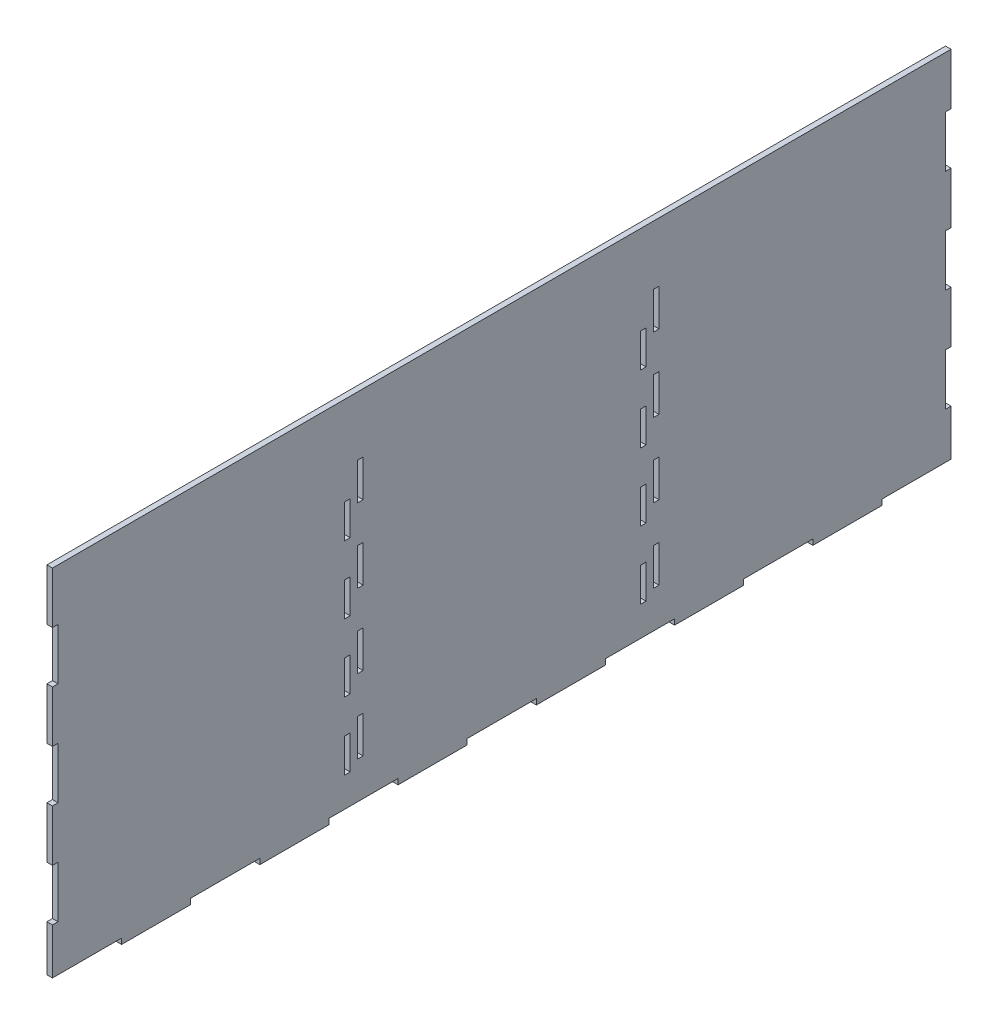
SolidWorks part; units mm, degrees
material "Acrylic (Medium-high impact)"
ref_plane "Front Plane" through (0, 0, 0) normal (0, 0, 1) x (1, 0, 0)
ref_plane "Top Plane" through (0, 0, 0) normal (0, 1, 0) x (1, 0, 0)
ref_plane "Right Plane" through (0, 0, 0) normal (1, 0, 0) x (0, 0, -1)
sketch "Sketch1" plane through (0, 0, 0) normal (1, 0, 0) x (0, 0, -1)
  line L0 (0, 152.4) -> (0, -152.4) construction
  line L1 (-381, 152.4) -> (381, 152.4)
  line L2 (-381, 152.4) -> (-381, -152.4)
  line L3 (-381, -152.4) -> (381, -152.4)
  line L4 (381, 152.4) -> (381, -152.4)
  line L5 (-381, 108.1768) -> (-381, 63.9536)
  line L10 (-381, 152.4) -> (-385.7625, 152.4)
  line L11 (-381, 152.4) -> (-381, 108.1768)
  line L12 (-381, 108.1768) -> (-385.7625, 108.1768)
  line L13 (-385.7625, 152.4) -> (-385.7625, 108.1768)
  line L14 (381, 152.4) -> (385.7625, 152.4)
  line L15 (381, 152.4) -> (381, 108.1768)
  line L16 (381, 108.1768) -> (385.7625, 108.1768)
  line L17 (385.7625, 152.4) -> (385.7625, 108.1768)
  line L18 (-385.7625, -152.4) -> (-326.4144, -152.4)
  line L19 (-385.7625, -152.4) -> (-385.7625, -157.1625)
  line L20 (-385.7625, -157.1625) -> (-326.4144, -157.1625)
  line L21 (-326.4144, -152.4) -> (-326.4144, -157.1625)
  line L22 (-381, 108.1768) -> (-385.7625, 108.1768)
  line L23 (-385.7625, 108.1768) -> (-385.7625, 63.9536)
  line L24 (-381, 63.9536) -> (-385.7625, 63.9536)
  line L25 (381, 108.1768) -> (381, 63.9536)
  line L26 (381, 108.1768) -> (385.7625, 108.1768)
  line L27 (385.7625, 108.1768) -> (385.7625, 63.9536)
  line L28 (381, 63.9536) -> (385.7625, 63.9536)
  line L29 (-381, 63.9536) -> (-381, 19.7304)
  line L30 (-381, 63.9536) -> (-385.7625, 63.9536)
  line L31 (-385.7625, 63.9536) -> (-385.7625, 19.7304)
  line L32 (-381, 19.7304) -> (-385.7625, 19.7304)
  line L33 (381, 63.9536) -> (381, 19.7304)
  line L34 (381, 63.9536) -> (385.7625, 63.9536)
  line L35 (385.7625, 63.9536) -> (385.7625, 19.7304)
  line L36 (381, 19.7304) -> (385.7625, 19.7304)
  line L37 (-381, 19.7304) -> (-381, -24.4929)
  line L38 (-381, 19.7304) -> (-385.7625, 19.7304)
  line L39 (-385.7625, 19.7304) -> (-385.7625, -24.4929)
  line L40 (-381, -24.4929) -> (-385.7625, -24.4929)
  line L41 (381, 19.7304) -> (381, -24.4929)
  line L42 (381, 19.7304) -> (385.7625, 19.7304)
  line L43 (385.7625, 19.7304) -> (385.7625, -24.4929)
  line L44 (381, -24.4929) -> (385.7625, -24.4929)
  line L45 (-381, -24.4929) -> (-381, -68.7161)
  line L46 (-381, -24.4929) -> (-385.7625, -24.4929)
  line L47 (-385.7625, -24.4929) -> (-385.7625, -68.7161)
  line L48 (-381, -68.7161) -> (-385.7625, -68.7161)
  line L49 (381, -24.4929) -> (381, -68.7161)
  line L50 (381, -24.4929) -> (385.7625, -24.4929)
  line L51 (385.7625, -24.4929) -> (385.7625, -68.7161)
  line L52 (381, -68.7161) -> (385.7625, -68.7161)
  line L53 (-381, -68.7161) -> (-381, -112.9393)
  line L54 (-381, -68.7161) -> (-385.7625, -68.7161)
  line L55 (-385.7625, -68.7161) -> (-385.7625, -112.9393)
  line L56 (-381, -112.9393) -> (-385.7625, -112.9393)
  line L57 (381, -68.7161) -> (381, -112.9393)
  line L58 (381, -68.7161) -> (385.7625, -68.7161)
  line L59 (385.7625, -68.7161) -> (385.7625, -112.9393)
  line L60 (381, -112.9393) -> (385.7625, -112.9393)
  line L61 (-381, -112.9393) -> (-381, -157.1625)
  line L62 (-381, -112.9393) -> (-385.7625, -112.9393)
  line L63 (-385.7625, -112.9393) -> (-385.7625, -157.1625)
  line L64 (-381, -157.1625) -> (-385.7625, -157.1625)
  line L65 (381, -112.9393) -> (381, -157.1625)
  line L66 (381, -112.9393) -> (385.7625, -112.9393)
  line L67 (385.7625, -112.9393) -> (385.7625, -157.1625)
  line L68 (381, -157.1625) -> (385.7625, -157.1625)
  line L69 (-326.4144, -157.1625) -> (-267.0663, -157.1625)
  line L70 (-326.4144, -152.4) -> (-326.4144, -157.1625)
  line L71 (-326.4144, -152.4) -> (-267.0663, -152.4)
  line L72 (-267.0663, -152.4) -> (-267.0663, -157.1625)
  line L73 (-267.0663, -157.1625) -> (-207.7183, -157.1625)
  line L74 (-267.0663, -152.4) -> (-267.0663, -157.1625)
  line L75 (-267.0663, -152.4) -> (-207.7183, -152.4)
  line L76 (-207.7183, -152.4) -> (-207.7183, -157.1625)
  line L77 (-207.7183, -157.1625) -> (-148.3702, -157.1625)
  line L78 (-207.7183, -152.4) -> (-207.7183, -157.1625)
  line L79 (-207.7183, -152.4) -> (-148.3702, -152.4)
  line L80 (-148.3702, -152.4) -> (-148.3702, -157.1625)
  line L81 (-148.3702, -157.1625) -> (-89.0221, -157.1625)
  line L82 (-148.3702, -152.4) -> (-148.3702, -157.1625)
  line L83 (-148.3702, -152.4) -> (-89.0221, -152.4)
  line L84 (-89.0221, -152.4) -> (-89.0221, -157.1625)
  line L85 (-89.0221, -157.1625) -> (-29.674, -157.1625)
  line L86 (-89.0221, -152.4) -> (-89.0221, -157.1625)
  line L87 (-89.0221, -152.4) -> (-29.674, -152.4)
  line L88 (-29.674, -152.4) -> (-29.674, -157.1625)
  line L89 (-29.674, -157.1625) -> (29.674, -157.1625)
  line L90 (-29.674, -152.4) -> (-29.674, -157.1625)
  line L91 (-29.674, -152.4) -> (29.674, -152.4)
  line L92 (29.674, -152.4) -> (29.674, -157.1625)
  line L93 (29.674, -157.1625) -> (89.0221, -157.1625)
  line L94 (29.674, -152.4) -> (29.674, -157.1625)
  line L95 (29.674, -152.4) -> (89.0221, -152.4)
  line L96 (89.0221, -152.4) -> (89.0221, -157.1625)
  line L97 (89.0221, -157.1625) -> (148.3702, -157.1625)
  line L98 (89.0221, -152.4) -> (89.0221, -157.1625)
  line L99 (89.0221, -152.4) -> (148.3702, -152.4)
  line L100 (148.3702, -152.4) -> (148.3702, -157.1625)
  line L101 (148.3702, -157.1625) -> (207.7183, -157.1625)
  line L102 (148.3702, -152.4) -> (148.3702, -157.1625)
  line L103 (148.3702, -152.4) -> (207.7183, -152.4)
  line L104 (207.7183, -152.4) -> (207.7183, -157.1625)
  line L105 (207.7183, -157.1625) -> (267.0663, -157.1625)
  line L106 (207.7183, -152.4) -> (207.7183, -157.1625)
  line L107 (207.7183, -152.4) -> (267.0663, -152.4)
  line L108 (267.0663, -152.4) -> (267.0663, -157.1625)
  line L125 (-124.6188, 0) -> (124.6188, 0) construction
  line L126 (-129.3812, 41.956) -> (-124.6188, 41.956) construction
  line L127 (-129.3812, 41.956) -> (-129.3812, -41.956) construction
  line L128 (-129.3812, -41.956) -> (-124.6188, -41.956) construction
  line L129 (-124.6188, 41.956) -> (-124.6188, -41.956) construction
  line L138 (124.6188, 41.956) -> (129.3813, 41.956) construction
  line L139 (124.6188, 41.956) -> (124.6188, -41.956) construction
  line L140 (124.6188, -41.956) -> (129.3813, -41.956) construction
  line L141 (129.3813, 41.956) -> (129.3813, -41.956) construction
  line L143 (267.0663, -157.1625) -> (326.4144, -157.1625)
  line L144 (267.0663, -152.4) -> (267.0663, -157.1625)
  line L145 (267.0663, -152.4) -> (326.4144, -152.4)
  line L146 (326.4144, -152.4) -> (326.4144, -157.1625)
  line L147 (326.4144, -157.1625) -> (385.7625, -157.1625)
  line L148 (326.4144, -152.4) -> (326.4144, -157.1625)
  line L149 (326.4144, -152.4) -> (385.7625, -152.4)
  line L150 (385.7625, -152.4) -> (385.7625, -157.1625)
  point P6 (0, 0)
  point P113 (-127, 41.956)
  point P114 (127, 41.956)
  point P117 (0, 0)
  dimension "D1" = 762
  dimension "D2" = 304.8
  dimension "D3" = 771.525
  dimension "D4" = 309.5625
  dimension "D5" = 44.2232
  dimension "D7" = 59.3481
  dimension "D9" = 254
  dimension "D10" = 4.7625
  dimension "D6" = 7
  dimension "D8" = 13
extrude "Boss-Extrude1" add sketch "Sketch1" along normal blind 4.7625
sketch "Sketch3" plane through (4.7625, 0, 0) normal (1, 0, 0) x (0, 0, -1)
  line L0 (-130.175, -127) -> (-130.175, 76.2) construction
  line L5 (-134.9375, 76.2) -> (-130.175, 76.2)
  line L6 (-134.9375, 76.2) -> (-134.9375, 47.1714)
  line L7 (-134.9375, 47.1714) -> (-130.175, 47.1714)
  line L8 (-130.175, 76.2) -> (-130.175, 47.1714)
  line L9 (-119.0625, 101.6) -> (-123.825, 101.6)
  line L10 (-119.0625, 101.6) -> (-119.0625, 69.85)
  line L11 (-119.0625, 69.85) -> (-123.825, 69.85)
  line L12 (-123.825, 101.6) -> (-123.825, 69.85)
  line L13 (-381, -152.4) -> (381, -152.4) construction
  line L14 (-123.825, -152.4) -> (-123.825, 101.6) construction
  line L15 (-130.175, 76.2) -> (-123.825, 76.2) construction
  line L16 (-127, 41.956) -> (-127, 76.2) construction
  line L17 (-129.3812, 41.956) -> (-124.6188, 41.956) construction
  line L18 (-119.0625, 69.85) -> (-119.0625, 38.1)
  line L19 (-119.0625, 69.85) -> (-123.825, 69.85)
  line L20 (-123.825, 69.85) -> (-123.825, 38.1)
  line L21 (-119.0625, 38.1) -> (-123.825, 38.1)
  line L22 (-119.0625, 38.1) -> (-119.0625, 6.35)
  line L23 (-119.0625, 38.1) -> (-123.825, 38.1)
  line L24 (-123.825, 38.1) -> (-123.825, 6.35)
  line L25 (-119.0625, 6.35) -> (-123.825, 6.35)
  line L26 (-119.0625, 6.35) -> (-119.0625, -25.4)
  line L27 (-119.0625, 6.35) -> (-123.825, 6.35)
  line L28 (-123.825, 6.35) -> (-123.825, -25.4)
  line L29 (-119.0625, -25.4) -> (-123.825, -25.4)
  line L30 (-119.0625, -25.4) -> (-119.0625, -57.15)
  line L31 (-119.0625, -25.4) -> (-123.825, -25.4)
  line L32 (-123.825, -25.4) -> (-123.825, -57.15)
  line L33 (-119.0625, -57.15) -> (-123.825, -57.15)
  line L34 (-119.0625, -57.15) -> (-119.0625, -88.9)
  line L35 (-119.0625, -57.15) -> (-123.825, -57.15)
  line L36 (-123.825, -57.15) -> (-123.825, -88.9)
  line L37 (-119.0625, -88.9) -> (-123.825, -88.9)
  line L38 (-119.0625, -88.9) -> (-119.0625, -120.65)
  line L39 (-119.0625, -88.9) -> (-123.825, -88.9)
  line L40 (-123.825, -88.9) -> (-123.825, -120.65)
  line L41 (-119.0625, -120.65) -> (-123.825, -120.65)
  line L42 (-134.9375, 47.1714) -> (-134.9375, 18.1429)
  line L43 (-134.9375, 47.1714) -> (-130.175, 47.1714)
  line L44 (-130.175, 47.1714) -> (-130.175, 18.1429)
  line L45 (-134.9375, 18.1429) -> (-130.175, 18.1429)
  line L46 (-134.9375, 18.1429) -> (-134.9375, -10.8857)
  line L47 (-134.9375, 18.1429) -> (-130.175, 18.1429)
  line L48 (-130.175, 18.1429) -> (-130.175, -10.8857)
  line L49 (-134.9375, -10.8857) -> (-130.175, -10.8857)
  line L50 (-134.9375, -10.8857) -> (-134.9375, -39.9143)
  line L51 (-134.9375, -10.8857) -> (-130.175, -10.8857)
  line L52 (-130.175, -10.8857) -> (-130.175, -39.9143)
  line L53 (-134.9375, -39.9143) -> (-130.175, -39.9143)
  line L54 (-134.9375, -39.9143) -> (-134.9375, -68.9429)
  line L55 (-134.9375, -39.9143) -> (-130.175, -39.9143)
  line L56 (-130.175, -39.9143) -> (-130.175, -68.9429)
  line L57 (-134.9375, -68.9429) -> (-130.175, -68.9429)
  line L58 (-134.9375, -68.9429) -> (-134.9375, -97.9714)
  line L59 (-134.9375, -68.9429) -> (-130.175, -68.9429)
  line L60 (-130.175, -68.9429) -> (-130.175, -97.9714)
  line L61 (-134.9375, -97.9714) -> (-130.175, -97.9714)
  line L62 (-134.9375, -97.9714) -> (-134.9375, -127)
  line L63 (-134.9375, -97.9714) -> (-130.175, -97.9714)
  line L64 (-130.175, -97.9714) -> (-130.175, -127)
  line L65 (-134.9375, -127) -> (-130.175, -127)
  line L66 (-119.0625, -120.65) -> (-119.0625, -152.4)
  line L67 (-119.0625, -120.65) -> (-123.825, -120.65)
  line L68 (-123.825, -120.65) -> (-123.825, -152.4)
  line L69 (-119.0625, -152.4) -> (-123.825, -152.4)
  line L70 (119.0625, 76.2) -> (123.825, 76.2)
  line L71 (119.0625, 76.2) -> (119.0625, 47.1714)
  line L72 (119.0625, 47.1714) -> (123.825, 47.1714)
  line L73 (123.825, 76.2) -> (123.825, 47.1714)
  line L74 (134.9375, 101.6) -> (130.175, 101.6)
  line L75 (134.9375, 101.6) -> (134.9375, 69.85)
  line L76 (134.9375, 69.85) -> (130.175, 69.85)
  line L77 (130.175, 101.6) -> (130.175, 69.85)
  line L78 (134.9375, 69.85) -> (134.9375, 38.1)
  line L79 (134.9375, 69.85) -> (130.175, 69.85)
  line L80 (130.175, 69.85) -> (130.175, 38.1)
  line L81 (134.9375, 38.1) -> (130.175, 38.1)
  line L82 (134.9375, 38.1) -> (134.9375, 6.35)
  line L83 (134.9375, 38.1) -> (130.175, 38.1)
  line L84 (130.175, 38.1) -> (130.175, 6.35)
  line L85 (134.9375, 6.35) -> (130.175, 6.35)
  line L86 (134.9375, 6.35) -> (134.9375, -25.4)
  line L87 (134.9375, 6.35) -> (130.175, 6.35)
  line L88 (130.175, 6.35) -> (130.175, -25.4)
  line L89 (134.9375, -25.4) -> (130.175, -25.4)
  line L90 (134.9375, -25.4) -> (134.9375, -57.15)
  line L91 (134.9375, -25.4) -> (130.175, -25.4)
  line L92 (130.175, -25.4) -> (130.175, -57.15)
  line L93 (134.9375, -57.15) -> (130.175, -57.15)
  line L94 (134.9375, -57.15) -> (134.9375, -88.9)
  line L95 (134.9375, -57.15) -> (130.175, -57.15)
  line L96 (130.175, -57.15) -> (130.175, -88.9)
  line L97 (134.9375, -88.9) -> (130.175, -88.9)
  line L98 (134.9375, -88.9) -> (134.9375, -120.65)
  line L99 (134.9375, -88.9) -> (130.175, -88.9)
  line L100 (130.175, -88.9) -> (130.175, -120.65)
  line L101 (134.9375, -120.65) -> (130.175, -120.65)
  line L102 (119.0625, 47.1714) -> (119.0625, 18.1429)
  line L103 (119.0625, 47.1714) -> (123.825, 47.1714)
  line L104 (123.825, 47.1714) -> (123.825, 18.1429)
  line L105 (119.0625, 18.1429) -> (123.825, 18.1429)
  line L106 (119.0625, 18.1429) -> (119.0625, -10.8857)
  line L107 (119.0625, 18.1429) -> (123.825, 18.1429)
  line L108 (123.825, 18.1429) -> (123.825, -10.8857)
  line L109 (119.0625, -10.8857) -> (123.825, -10.8857)
  line L110 (119.0625, -10.8857) -> (119.0625, -39.9143)
  line L111 (119.0625, -10.8857) -> (123.825, -10.8857)
  line L112 (123.825, -10.8857) -> (123.825, -39.9143)
  line L113 (119.0625, -39.9143) -> (123.825, -39.9143)
  line L114 (119.0625, -39.9143) -> (119.0625, -68.9429)
  line L115 (119.0625, -39.9143) -> (123.825, -39.9143)
  line L116 (123.825, -39.9143) -> (123.825, -68.9429)
  line L117 (119.0625, -68.9429) -> (123.825, -68.9429)
  line L118 (119.0625, -68.9429) -> (119.0625, -97.9714)
  line L119 (119.0625, -68.9429) -> (123.825, -68.9429)
  line L120 (123.825, -68.9429) -> (123.825, -97.9714)
  line L121 (119.0625, -97.9714) -> (123.825, -97.9714)
  line L122 (119.0625, -97.9714) -> (119.0625, -127)
  line L123 (119.0625, -97.9714) -> (123.825, -97.9714)
  line L124 (123.825, -97.9714) -> (123.825, -127)
  line L125 (119.0625, -127) -> (123.825, -127)
  line L126 (134.9375, -120.65) -> (134.9375, -152.4)
  line L127 (134.9375, -120.65) -> (130.175, -120.65)
  line L128 (130.175, -120.65) -> (130.175, -152.4)
  line L129 (134.9375, -152.4) -> (130.175, -152.4)
  line L130 (123.825, -127) -> (123.825, 76.2) construction
  line L131 (130.175, -152.4) -> (130.175, 101.6) construction
  line L132 (123.825, 76.2) -> (130.175, 76.2) construction
  line L133 (127, 41.956) -> (127, 76.2) construction
  line L134 (124.6188, 41.956) -> (129.3813, 41.956) construction
  dimension "D1" = 203.2
  dimension "D2" = 254
  dimension "D3" = 25.4
  dimension "D4" = 6.35
  dimension "D5" = 4.7625
  dimension "D7" = 31.75
  dimension "D9" = 29.0286
  dimension "D6" = 8
  dimension "D8" = 7
  dimension "D10" = 2
extrude "Cut-Extrude1" cut sketch "Sketch3" against normal through all contours L41 L38 L37 L40 | L33 L30 L29 L32 | L25 L22 L21 L24 | L9 L12 L11 L10 | L8 L5 L6 L7 | L46 L49 L48 L45 | L54 L57 L56 L53 | L62 L65 L64 L61 | L74 L77 L76 L75 | L73 L70 L71 L72 | L85 L82 L81 L84 | L106 L109 L108 L105 | L93 L90 L89 L92 | L114 L117 L116 L113 | L101 L98 L97 L100 | L122 L125 L124 L121
equation "\"Height\"= 12in"
equation "\"Depth\"= 7in"
equation "\"WallThickness\"= 0.1875in"
equation "\"FloorThickness\"= 0.1875in"
equation "\"D2@Sketch1\"=\"Height\""
equation "\"D3@Sketch1\"=\"D1@Sketch1\"+2*\"WallThickness\""
equation "\"D4@Sketch1\"=\"D2@Sketch1\"+\"FloorThickness\""
equation "\"D5@Sketch1\"=\"D4@Sketch1\"/7"
equation "\"D7@Sketch1\"=\"D3@Sketch1\"/\"D8@Sketch1\""
equation "\"D1@Boss-Extrude1\"=\"WallThickness\""
equation "\"Width\"= 30in"
equation "\"D4@Sketch3\"=\"WallThickness\"+(1/16in)"
equation "\"D5@Sketch3\"=\"WallThickness\""
equation "\"D7@Sketch3\"=\"D2@Sketch3\"/\"D6@Sketch3\""
equation "\"D9@Sketch3\"=\"D1@Sketch3\"/\"D8@Sketch3\""
equation "\"D10@Sketch1\"=\"WallThickness\""
equation "\"D1@Sketch1\"=\"Width\""
